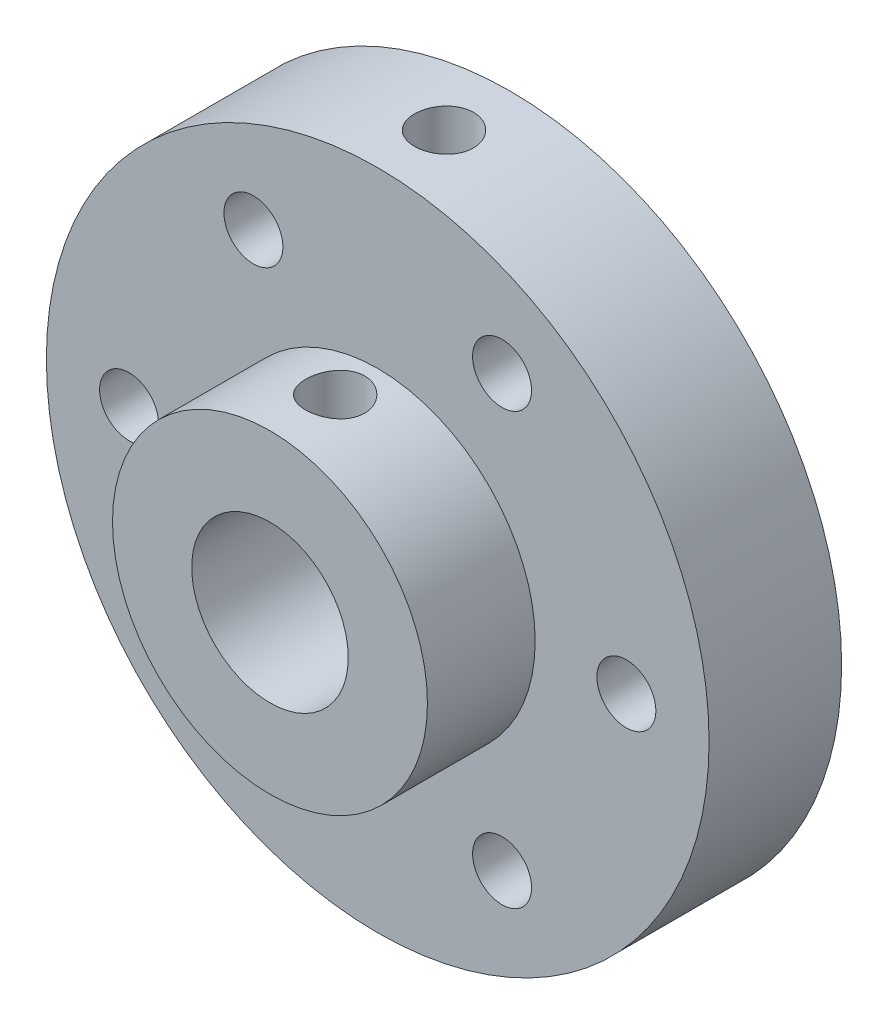
SolidWorks part; units mm, degrees
ref_plane "Alzado" through (0, 0, 0) normal (0, 0, 1) x (1, 0, 0)
ref_plane "Planta" through (0, 0, 0) normal (0, 1, 0) x (1, 0, 0)
ref_plane "Vista lateral" through (0, 0, 0) normal (1, 0, 0) x (0, 0, -1)
sketch "Croquis2" plane through (0, 0, 0) normal (1, 0, 0) x (0, 0, -1)
  line L0 (0, 0) -> (0, 6.035)
  line L1 (0, 6.035) -> (4.13, 6.035)
  line L2 (4.13, 6.035) -> (4.13, 12.7)
  line L3 (4.13, 12.7) -> (9.21, 12.7)
  line L4 (9.21, 12.7) -> (9.21, 0)
  line L5 (9.21, 0) -> (0, 0)
  dimension "D1" = 6.035
  dimension "D2" = 12.7
  dimension "D3" = 5.08
  dimension "D4" = 9.21
revolve "Revolución1" add sketch "Croquis2" angle 360 about L5
sketch "Croquis3" plane through (0, 0, 0) normal (0, 0, 1) x (1, 0, 0)
  circle A0 centre (0, 0) radius 3
  dimension "D1" = 6
extrude "Cortar-Extruir1" cut sketch "Croquis3" against normal through all
hole_wizard "Taladro roscado #4-403" positions "Croquis8" profile "Croquis7" tap size "#4-40" standard "Ansi Inch" end condition through all
sketch "Croquis8" plane through (0, 0, -4.13) normal (0, 0, 1) x (1, 0, 0)
  circle A0 centre (0, 0) radius 9.53 construction
  point P8 (-9.53, 0)
  point P16 (-4.765, 8.2532)
  point P17 (4.765, 8.2532)
  point P18 (9.53, 0)
  point P19 (4.765, -8.2532)
  point P20 (-4.765, -8.2532)
  point P21 (0, 0)
  dimension "D1" = 19.06
  dimension "D2" = 6
sketch "Croquis7" plane through (-9.53, 0, -4.13) normal (1, 0, 0) x (0, -1, 0)
  line L0 (0, 0) -> (0, 5.08)
  line L1 (0, 5.08) -> (1.1303, 5.08)
  line L2 (1.1303, 5.08) -> (1.1303, 0)
  line L5 (1.1303, 0) -> (0, 0)
  line L11 (0, -6.35) -> (0, 107.95) construction
  dimension "Diámetro de perforador para roscar hasta el siguiente" = 2.2606
  dimension "Profundidad de perforador para roscar hasta el siguiente" = 5.08
cosmetic thread "Rosca de taladro13" parameters "D2"=2.8448
cosmetic thread "Rosca de taladro14" parameters "D2"=2.8448
cosmetic thread "Rosca de taladro15" parameters "D2"=2.8448
cosmetic thread "Rosca de taladro16" parameters "D2"=2.8448
cosmetic thread "Rosca de taladro17" parameters "D2"=2.8448
cosmetic thread "Rosca de taladro18" parameters "D2"=2.8448
ref_plane "Plano1" through (0, 12.7, 0) normal (0, 1, 0) x (1, 0, 0)
hole_wizard "Taladro roscado #4-404" positions "Croquis10" profile "Croquis9" tap size "#4-40" standard "Ansi Inch"
sketch "Croquis10" plane through (0, 12.7, 0) normal (0, 1, 0) x (1, 0, 0)
  line L7 (12.7, 9.21) -> (-12.7, 9.21) construction
  point P0 (0, 6.67)
  point P2 (0, 2.5)
  dimension "D1" = 2.54
  dimension "D2" = 2.5
sketch "Croquis9" plane through (0, 12.7, -6.67) normal (1, 0, 0) x (0, 0, 1)
  line L0 (0, 0) -> (0, 13.3782)
  line L1 (0, 13.3782) -> (1.1303, 12.699)
  line L2 (1.1303, 12.699) -> (1.1303, 0)
  line L5 (1.1303, 0) -> (0, 0)
  line L10 (0, 13.3782) -> (-1.1303, 12.699) construction
  line L11 (0, -6.35) -> (0, 107.95) construction
  dimension "Diámetro de perforador para roscar" = 2.2606
  dimension "Profundidad de perforador para roscar" = 12.699
  dimension "Ángulo de perforador" = 118
cosmetic thread "Rosca de taladro19" parameters "D1"=5.69, "D2"=2.8448
cosmetic thread "Rosca de taladro20" parameters "D1"=5.69, "D2"=2.8448
